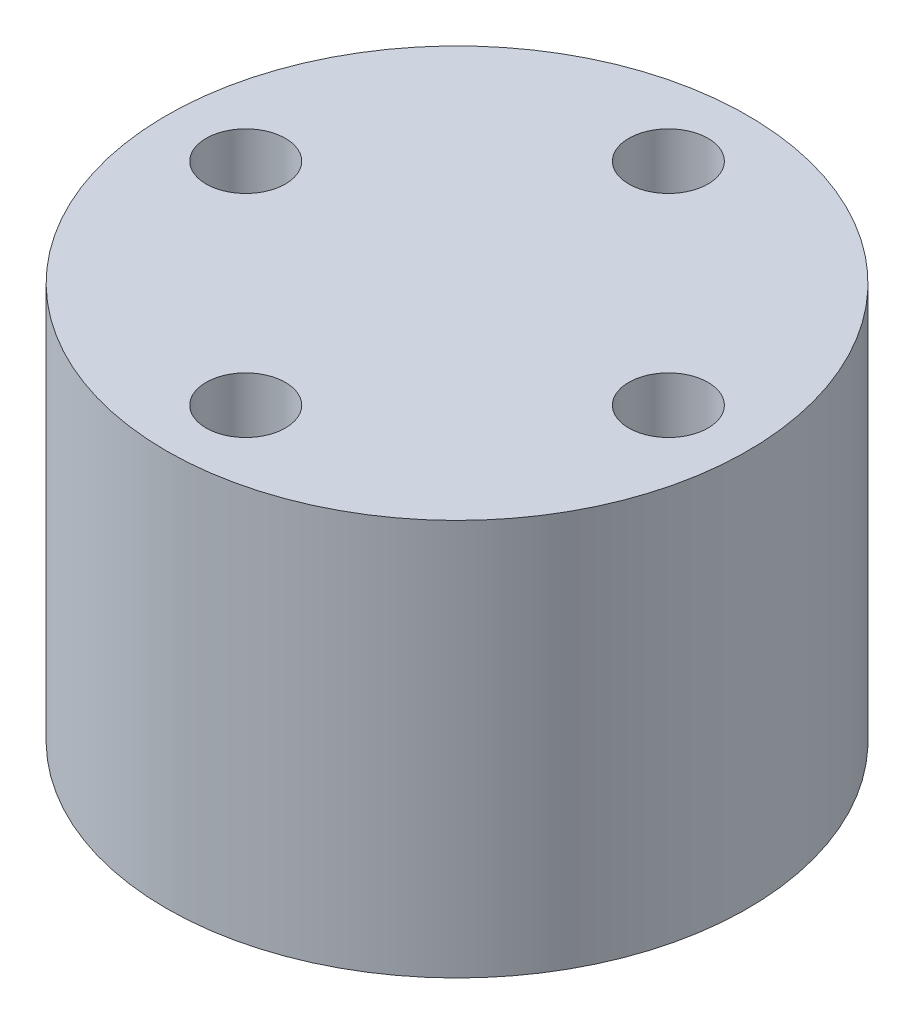
SolidWorks part; units mm, degrees
ref_plane "前视基准面" through (0, 0, 0) normal (0, 0, 1) x (1, 0, 0)
ref_plane "上视基准面" through (0, 0, 0) normal (0, 1, 0) x (1, 0, 0)
ref_plane "右视基准面" through (0, 0, 0) normal (1, 0, 0) x (0, 0, -1)
other "Configuration Table"
sketch "草图1" plane through (0, 0, 0) normal (0, 1, 0) x (1, 0, 0)
  line L0 (0, 18.1092) -> (0, -16.3823) construction
  circle A0 centre (0, 0) radius 11
  circle A1 centre (0, 0) radius 8 construction
  circle A2 centre (0, 8) radius 1.5
  circle A3 centre (8, 0) radius 1.5
  circle A4 centre (0, -8) radius 1.5
  circle A5 centre (-8, 0) radius 1.5
  point P17 (0, 0)
  dimension "D1" = 22
  dimension "D2" = 16
  dimension "D3" = 3
  dimension "D4" = 4
extrude "凸台-拉伸1" add sketch "草图1" along normal blind 15
